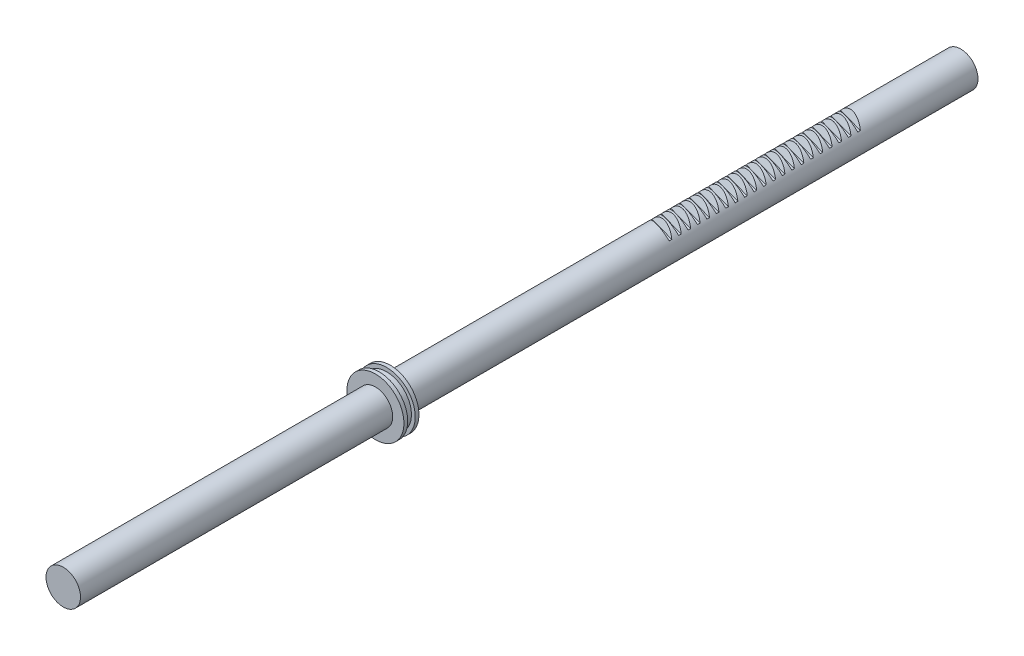
SolidWorks part; units mm, degrees
material "1.0718 (11SMnPb30)"
ref_plane "Ön Düzlem" through (0, 0, 0) normal (0, 0, 1) x (1, 0, 0)
ref_plane "Üst Düzlem" through (0, 0, 0) normal (0, 1, 0) x (1, 0, 0)
ref_plane "Sağ Düzlem" through (0, 0, 0) normal (1, 0, 0) x (0, 0, -1)
sketch "Çizim5" plane through (0, 0, 0) normal (0, 0, 1) x (1, 0, 0)
  circle A0 centre (0, 0) radius 11.5
extrude "Yükseklik-Ekstrüzyon2" add sketch "Çizim5" along normal blind 598
ref_plane "Düzlem1" through (11.5, 0, 0) normal (1, 0, 0) x (0, 0, -1)
sketch "Çizim6" plane through (11.5, 0, 0) normal (1, 0, 0) x (0, 0, -1)
  line L0 (0, -11.5) -> (0, 11.5) construction
  line L1 (0, 11.5) -> (-598, 11.5) construction
  line L2 (-78.3621, 7) -> (-80, 11.5)
  line L3 (-80, 11.5) -> (-81.2837, 11.5)
  line L4 (-81.2837, 11.5) -> (-82.9216, 7)
  line L5 (-82.9216, 7) -> (-84.6453, 7)
  line L6 (-84.6453, 7) -> (-86.2832, 11.5)
  line L7 (-86.2832, 11.5) -> (-87.5669, 11.5)
  line L8 (-87.5669, 11.5) -> (-89.2048, 7)
  line L9 (-89.2048, 7) -> (-90.9285, 7)
  line L10 (-90.9285, 7) -> (-92.5664, 11.5)
  line L11 (-92.5664, 11.5) -> (-93.8501, 11.5)
  line L12 (-93.8501, 11.5) -> (-95.4879, 7)
  line L13 (-95.4879, 7) -> (-97.2117, 7)
  line L14 (-97.2117, 7) -> (-98.8496, 11.5)
  line L15 (-98.8496, 11.5) -> (-100.1333, 11.5)
  line L16 (-100.1333, 11.5) -> (-101.7711, 7)
  line L17 (-101.7711, 7) -> (-103.4949, 7)
  line L18 (-103.4949, 7) -> (-105.1327, 11.5)
  line L19 (-105.1327, 11.5) -> (-106.4165, 11.5)
  line L20 (-106.4165, 11.5) -> (-108.0543, 7)
  line L21 (-108.0543, 7) -> (-109.7781, 7)
  line L22 (-109.7781, 7) -> (-111.4159, 11.5)
  line L23 (-111.4159, 11.5) -> (-112.6996, 11.5)
  line L24 (-112.6996, 11.5) -> (-114.3375, 7)
  line L25 (-114.3375, 7) -> (-116.0612, 7)
  line L26 (-116.0612, 7) -> (-117.6991, 11.5)
  line L27 (-117.6991, 11.5) -> (-118.9828, 11.5)
  line L28 (-118.9828, 11.5) -> (-120.6207, 7)
  line L29 (-120.6207, 7) -> (-122.3444, 7)
  line L30 (-122.3444, 7) -> (-123.9823, 11.5)
  line L31 (-123.9823, 11.5) -> (-125.266, 11.5)
  line L32 (-125.266, 11.5) -> (-126.9039, 7)
  line L33 (-126.9039, 7) -> (-128.6276, 7)
  line L34 (-128.6276, 7) -> (-130.2655, 11.5)
  line L35 (-130.2655, 11.5) -> (-131.5492, 11.5)
  line L36 (-131.5492, 11.5) -> (-133.1871, 7)
  line L37 (-133.1871, 7) -> (-134.9108, 7)
  line L38 (-134.9108, 7) -> (-136.5487, 11.5)
  line L39 (-136.5487, 11.5) -> (-137.8324, 11.5)
  line L40 (-137.8324, 11.5) -> (-139.4702, 7)
  line L41 (-139.4702, 7) -> (-141.194, 7)
  line L42 (-141.194, 7) -> (-142.8319, 11.5)
  line L43 (-142.8319, 11.5) -> (-144.1156, 11.5)
  line L44 (-144.1156, 11.5) -> (-145.7534, 7)
  line L45 (-145.7534, 7) -> (-147.4772, 7)
  line L46 (-147.4772, 7) -> (-149.115, 11.5)
  line L47 (-149.115, 11.5) -> (-150.3988, 11.5)
  line L48 (-150.3988, 11.5) -> (-152.0366, 7)
  line L49 (-152.0366, 7) -> (-153.7604, 7)
  line L50 (-153.7604, 7) -> (-155.3982, 11.5)
  line L51 (-155.3982, 11.5) -> (-156.6819, 11.5)
  line L52 (-156.6819, 11.5) -> (-158.3198, 7)
  line L53 (-158.3198, 7) -> (-160.0435, 7)
  line L54 (-160.0435, 7) -> (-161.6814, 11.5)
  line L55 (-161.6814, 11.5) -> (-162.9651, 11.5)
  line L56 (-162.9651, 11.5) -> (-164.603, 7)
  line L57 (-164.603, 7) -> (-166.3267, 7)
  line L58 (-166.3267, 7) -> (-167.9646, 11.5)
  line L59 (-167.9646, 11.5) -> (-169.2483, 11.5)
  line L60 (-169.2483, 11.5) -> (-170.8862, 7)
  line L61 (-170.8862, 7) -> (-172.6099, 7)
  line L62 (-172.6099, 7) -> (-174.2478, 11.5)
  line L63 (-174.2478, 11.5) -> (-175.5315, 11.5)
  line L64 (-175.5315, 11.5) -> (-177.1694, 7)
  line L65 (-177.1694, 7) -> (-178.8931, 7)
  line L66 (-178.8931, 7) -> (-180.531, 11.5)
  line L67 (-180.531, 11.5) -> (-181.8147, 11.5)
  line L68 (-181.8147, 11.5) -> (-183.4525, 7)
  line L69 (-183.4525, 7) -> (-185.1763, 7)
  line L70 (-185.1763, 7) -> (-186.8142, 11.5)
  line L71 (-186.8142, 11.5) -> (-188.0979, 11.5)
  line L72 (-188.0979, 11.5) -> (-189.7357, 7)
  line L73 (-189.7357, 7) -> (-191.4595, 7)
  line L74 (-191.4595, 7) -> (-193.0973, 11.5)
  line L75 (-193.0973, 11.5) -> (-194.381, 11.5)
  line L76 (-194.381, 11.5) -> (-196.0189, 7)
  line L77 (-196.0189, 7) -> (-197.7427, 7)
  line L78 (-197.7427, 7) -> (-199.3805, 11.5)
  line L79 (-199.3805, 11.5) -> (-200.6642, 11.5)
  line L80 (-200.6642, 11.5) -> (-202.3021, 7)
  line L81 (-78.3621, 7) -> (-76.6421, 7)
  line L82 (-76.6421, 7) -> (-74.4318, 13.0727)
  line L83 (-202.3021, 7) -> (-204.0221, 7)
  line L84 (-204.0221, 7) -> (-206.2324, 13.0727)
  line L85 (-206.2324, 13.0727) -> (-74.4318, 13.0727)
  dimension "D1" = 110
  dimension "D2" = 80
sketch "Çizim7" plane through (0, 0, 0) normal (0, 1, 0) x (1, 0, 0)
  line L0 (25.1541, -50.7969) -> (-17.1418, -39.0434)
  line L1 (11.5, 0) -> (-11.5, 0) construction
  dimension "D1" = 15.53
sweep "Kes-Süpür2" cut profiles "Çizim6" path "Çizim7"
sketch "Çizim8" plane through (0, 0, 0) normal (0, 1, 0) x (1, 0, 0)
  line L0 (0, 0) -> (0, -598) construction
  line L1 (-11.5, -598) -> (11.5, -598) construction
sketch "Çizim11" plane through (0, 0, 0) normal (1, 0, 0) x (0, 0, -1)
  line L0 (-380, 19) -> (-380, 11.5)
  line L1 (-382.5, 19) -> (-380, 19)
  line L2 (-382.5, 16.5) -> (-382.5, 19)
  line L3 (-387.5, 16.5) -> (-382.5, 16.5)
  line L4 (-387.5, 19) -> (-387.5, 16.5)
  line L5 (-390, 19) -> (-387.5, 19)
  line L6 (-390, 19) -> (-390, 11.5)
  line L7 (-390, 11.5) -> (-380, 11.5)
  line L8 (-598, 11.5) -> (-598, -11.5) construction
  dimension "D1" = 208
  dimension "D2" = 2.5
  dimension "D3" = 2.5
  dimension "D4" = 5
  dimension "D5" = 7.5
  dimension "D6" = 2.5
revolve "Döndür1" add sketch "Çizim11" angle 360 about L0
sketch "Çizim12" plane through (0, 0, 0) normal (0, 0, -1) x (-1, 0, 0)
  circle A0 centre (0, -3.4) radius 3.4
  dimension "D1" = 6.8
extrude "Kes-Ekstrüzyon1" cut sketch "Çizim12" against normal blind 387
